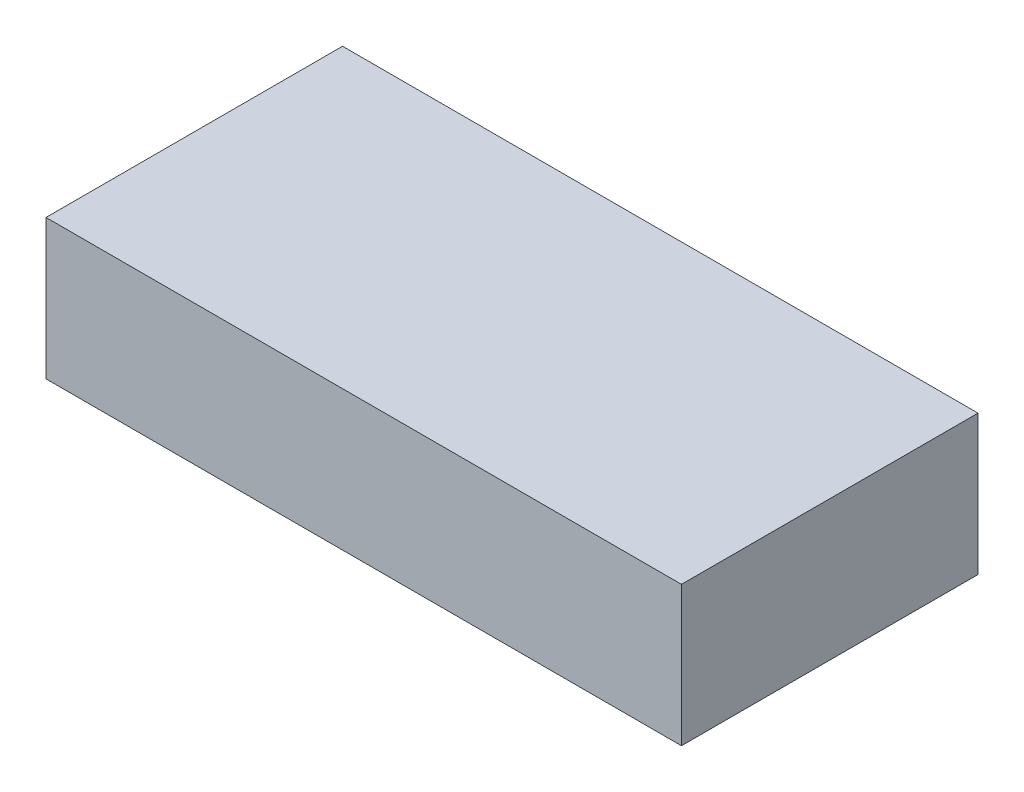
SolidWorks part; units mm, degrees
ref_plane "Front Plane" through (0, 0, 0) normal (0, 0, 1) x (1, 0, 0)
ref_plane "Top Plane" through (0, 0, 0) normal (0, 1, 0) x (1, 0, 0)
ref_plane "Right Plane" through (0, 0, 0) normal (1, 0, 0) x (0, 0, -1)
sketch "Sketch1" plane through (0, 0, 0) normal (0, 1, 0) x (1, 0, 0)
  line L1 (19.05, -8.89) -> (-19.05, -8.89)
  line L2 (19.05, -8.89) -> (19.05, 8.89)
  line L3 (19.05, 8.89) -> (-19.05, 8.89)
  line L4 (-19.05, -8.89) -> (-19.05, 8.89)
  line L5 (19.05, -8.89) -> (-19.05, 8.89) construction
  line L6 (19.05, 8.89) -> (-19.05, -8.89) construction
  point P0 (0, 0)
extrude "Boss-Extrude1" add sketch "Sketch1" along normal blind 8.382
